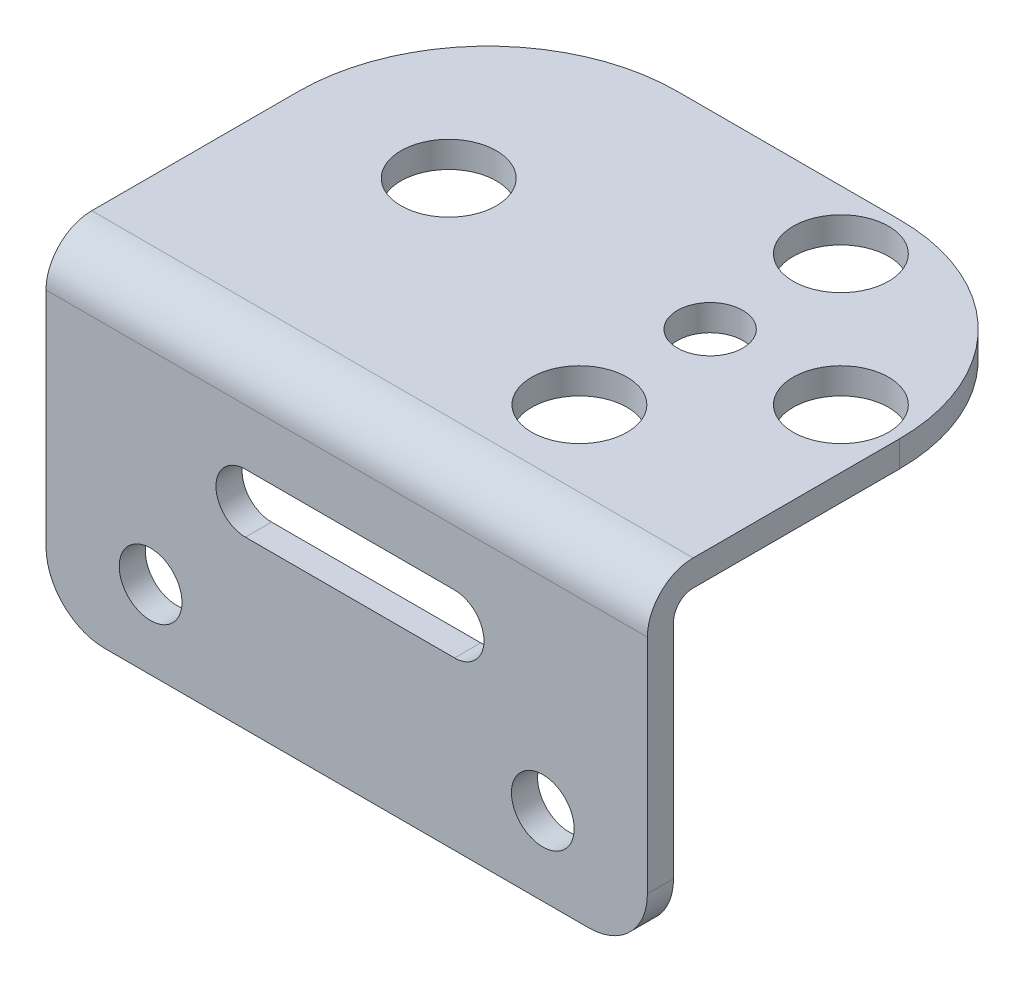
SolidWorks part; units mm, degrees
material "6061 合金"
ref_plane "前视基准面" through (0, 0, 0) normal (0, 0, 1) x (1, 0, 0)
ref_plane "上视基准面" through (0, 0, 0) normal (0, 1, 0) x (1, 0, 0)
ref_plane "右视基准面" through (0, 0, 0) normal (1, 0, 0) x (0, 0, -1)
other "Configuration Table"
sketch "草图3" plane through (0, 0, 0) normal (0, 1, 0) x (1, 0, 0)
  line L0 (0, 0) -> (46, 0)
  line L1 (46, 0) -> (46, 33.8)
  line L2 (46, 33.8) -> (0, 33.8)
  line L3 (0, 33.8) -> (0, 0)
  dimension "D1" = 33.8
  dimension "D2" = 46
extrude "凸台-拉伸1" add sketch "草图3" along normal blind 2
fillet "圆角1" radius 14.5 2 edges at (0, 1, -33.8) (46, 1, -33.8)
sketch "草图4" plane through (0, 2, 0) normal (0, 1, 0) x (1, 0, 0)
  line L0 (31.5, 33.8) -> (31.5, 0) construction
  line L1 (0, 0) -> (46, 0) construction
  line L2 (46, 19.3) -> (0, 19.3) construction
  circle A0 centre (31.5, 19.3) radius 2.5
  circle A1 centre (41.5, 19.3) radius 3.65
  circle A2 centre (31.5, 29.3) radius 3.65
  circle A3 centre (31.5, 9.3) radius 3.65
  circle A4 centre (11.5, 19.3) radius 3.65
  point P5 (46, 19.3)
  point P9 (31.5, 19.3)
  point P14 (46, 19.3)
  dimension "D1" = 5
  dimension "D2" = 7.3
  dimension "D4" = 7.3
  dimension "D5" = 7.3
  dimension "D8" = 7.3
  dimension "D3" = 10
  dimension "D6" = 10
  dimension "D7" = 10
  dimension "D9" = 20
extrude "切除-拉伸1" cut sketch "草图4" against normal blind 2
sketch "草图5" plane through (0, 0, 0) normal (0, -1, 0) x (1, 0, 0)
  line L0 (0, 0) -> (46, 0)
  line L1 (46, 0) -> (46, -2)
  line L2 (46, 0) -> (46, -19.3) construction
  line L3 (46, -2) -> (0, -2)
  line L4 (0, -2) -> (0, 0)
  dimension "D1" = 2
extrude "凸台-拉伸2" add sketch "草图5" along normal blind 23
fillet "圆角2" radius 4.5 2 edges at (0, -23, -1) (46, -23, -1)
fillet "圆角3" radius 3.5 1 edges at (23, 2, 0)
fillet "圆角4" radius 1.5 1 edges at (23, 0, -2)
sketch "草图6" plane through (0, 0, 0) normal (0, 0, 1) x (1, 0, 0)
  line L0 (0, -17) -> (46, -17) construction
  line L1 (0, -1.5) -> (0, -18.5) construction
  line L2 (46, -1.5) -> (46, -18.5) construction
  line L3 (41.5, -23) -> (4.5, -23) construction
  line L4 (0, -8) -> (46, -8) construction
  line L5 (15.25, -8) -> (31.25, -8) construction
  line L6 (15.25, -5.75) -> (31.25, -5.75)
  line L7 (15.25, -10.25) -> (31.25, -10.25)
  circle A0 centre (8, -17) radius 2.4
  circle A1 centre (38, -17) radius 2.4
  arc A2 (15.25, -5.75) -> (15.25, -10.25) centre (15.25, -8) ccw
  arc A3 (31.25, -10.25) -> (31.25, -5.75) centre (31.25, -8) ccw
  point P16 (23.25, -8)
  point P21 (13, -8)
  point P22 (33.5, -8)
  dimension "D2" = 4.8
  dimension "D3" = 4.8
  dimension "D1" = 6
  dimension "D4" = 8
  dimension "D5" = 8
  dimension "D6" = 15
  dimension "D7" = 20.5
  dimension "D8" = 4.5
  dimension "D9" = 23.25
extrude "切除-拉伸2" cut sketch "草图6" against normal blind 25
